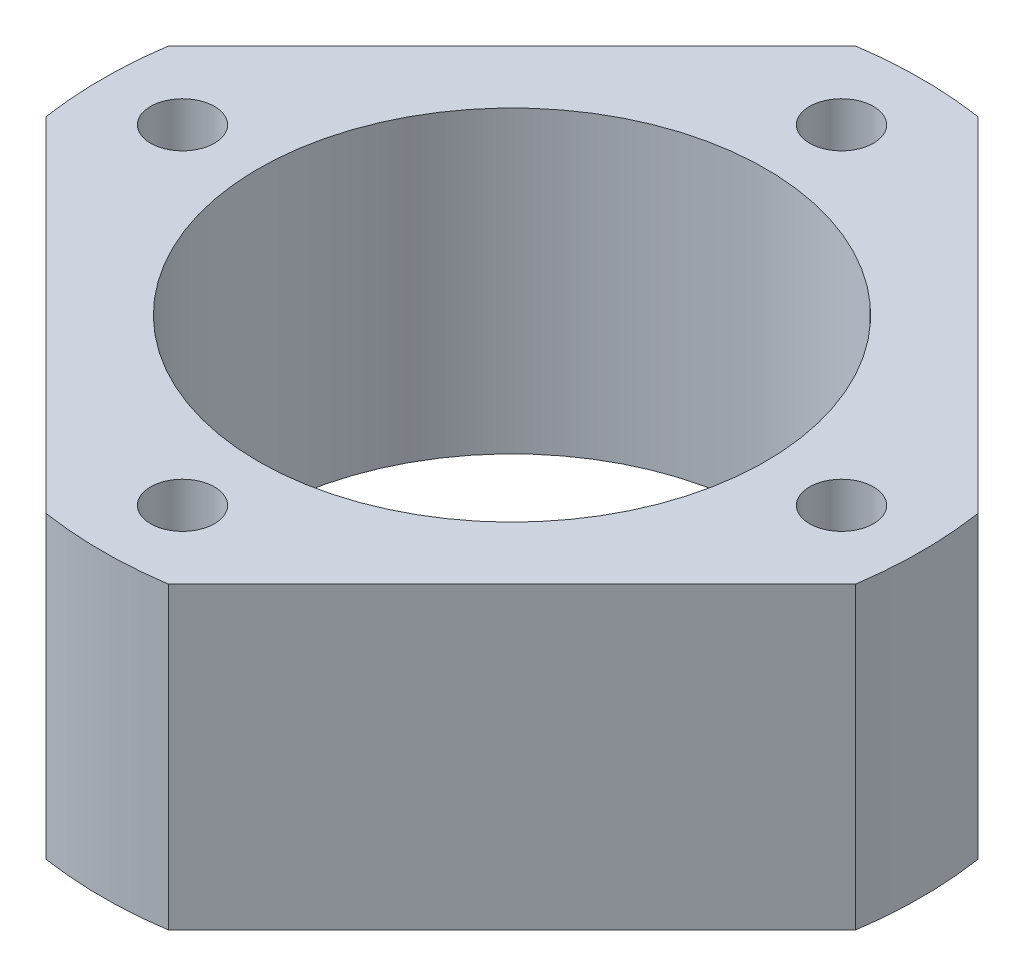
SolidWorks part; units mm, degrees
ref_plane "前视基准面" through (0, 0, 0) normal (0, 0, 1) x (1, 0, 0)
ref_plane "上视基准面" through (0, 0, 0) normal (0, 1, 0) x (1, 0, 0)
ref_plane "右视基准面" through (0, 0, 0) normal (1, 0, 0) x (0, 0, -1)
sketch "草图1" plane through (0, 0, 0) normal (0, 1, 0) x (1, 0, 0)
  line L0 (-20.2696, 3.0649) -> (-3.0649, 20.2696)
  line L1 (-11.6673, 11.6673) -> (0, 0) construction
  line L3 (0, 20.5) -> (0, 0) construction
  line L4 (3.0649, 20.2696) -> (20.2696, 3.0649)
  line L5 (20.2696, -3.0649) -> (3.0649, -20.2696)
  line L6 (-3.0649, -20.2696) -> (-20.2696, -3.0649)
  circle A0 centre (0, 0) radius 12.7
  circle A1 centre (0, 0) radius 20.5
  circle A2 centre (0, 0) radius 16.5 construction
  circle A3 centre (0, 16.5) radius 1.6
  circle A4 centre (16.5, 0) radius 1.6
  circle A5 centre (0, -16.5) radius 1.6
  circle A6 centre (-16.5, 0) radius 1.6
  point P16 (0, 0)
  point P17 (19.869, -8.6469)
  point P18 (0, 0)
  point P27 (0, 0)
  dimension "D1" = 25.4
  dimension "D2" = 41
  dimension "D3" = 33
  dimension "D4" = 3.2
  dimension "D6" = 45
  dimension "D5" = 4
  dimension "D7" = 4
extrude "凸台-拉伸1" add sketch "草图1" along normal blind 15 contours L5 A1 L4 L0 L6 A6 A5 A4 A3 A0
